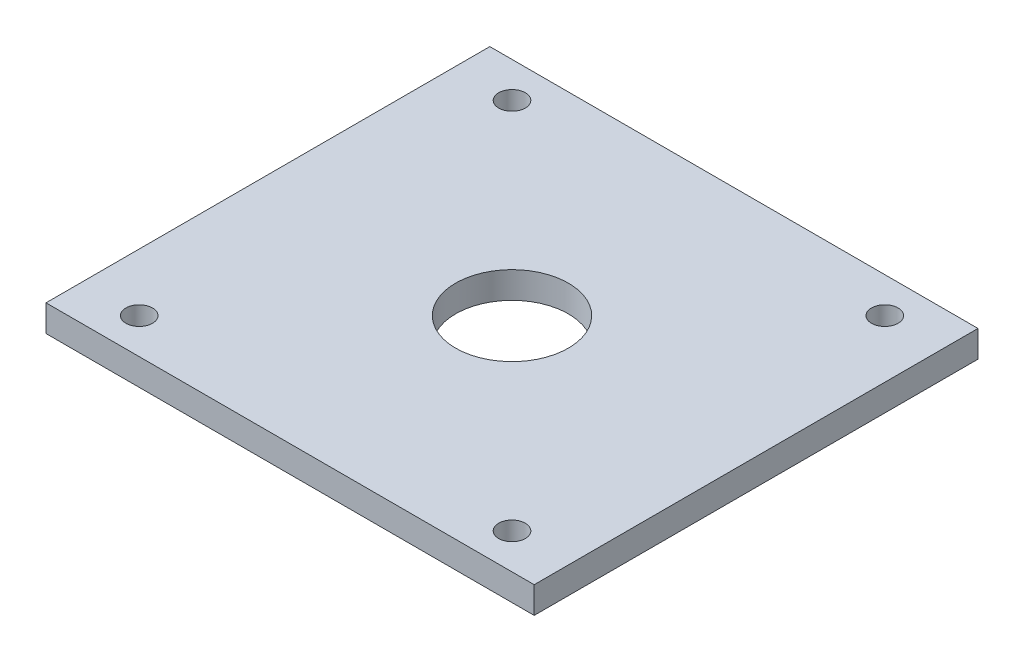
SolidWorks part; units mm, degrees
ref_plane "Alzado" through (0, 0, 0) normal (0, 0, 1) x (1, 0, 0)
ref_plane "Planta" through (0, 0, 0) normal (0, 1, 0) x (1, 0, 0)
ref_plane "Vista lateral" through (0, 0, 0) normal (1, 0, 0) x (0, 0, -1)
sketch "Sketch1" plane through (0, 0, 0) normal (0, 1, 0) x (1, 0, 0)
  line L1 (-27.5, 25) -> (27.5, 25)
  line L2 (-27.5, 25) -> (-27.5, -25)
  line L3 (-27.5, -25) -> (27.5, -25)
  line L4 (27.5, 25) -> (27.5, -25)
  line L5 (-27.5, 25) -> (27.5, -25) construction
  line L6 (-27.5, -25) -> (27.5, 25) construction
  point P0 (0, 0)
  dimension "D1" = 50
  dimension "D2" = 55
extrude "Boss-Extrude1" add sketch "Sketch1" along normal blind 3
sketch "Sketch2" plane through (0, 3, 0) normal (0, 1, 0) x (1, 0, 0)
  circle A0 centre (0, 0) radius 6.35
  dimension "D1" = 12.7
extrude "Cut-Extrude1" cut sketch "Sketch2" against normal through all contours A0
sketch "Sketch3" plane through (0, 3, 0) normal (0, 1, 0) x (1, 0, 0)
  line L1 (-21, 21) -> (21, 21) construction
  line L2 (-21, 21) -> (-21, -21) construction
  line L3 (-21, -21) -> (21, -21) construction
  line L4 (21, 21) -> (21, -21) construction
  line L5 (-21, 21) -> (21, -21) construction
  line L6 (-21, -21) -> (21, 21) construction
  circle A0 centre (-21, 21) radius 1.5
  point P0 (0, 0)
  dimension "D2" = 3
  dimension "D1" = 42
extrude "Cut-Extrude2" cut sketch "Sketch3" against normal through all
pattern_circular "CirPattern1" count 4 over 360 about axis through (0, 0, 0) along (0, 1, 0) of "Cut-Extrude2"
